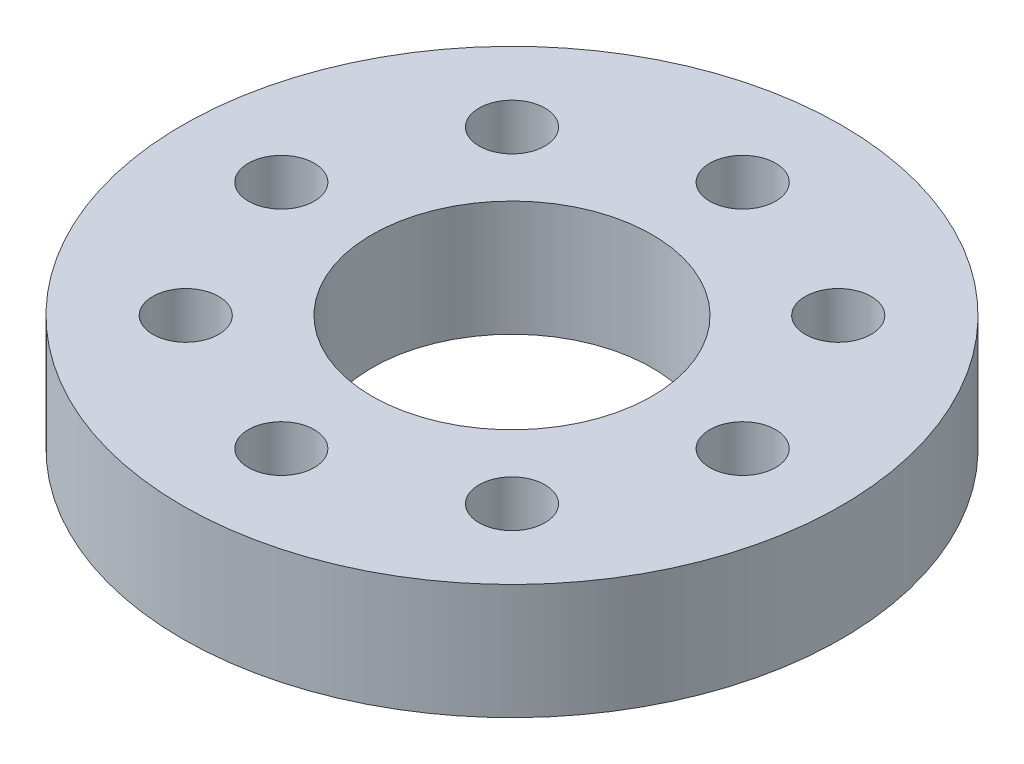
SolidWorks part; units mm, degrees
material "ABS PC"
ref_plane "Front Plane" through (0, 0, 0) normal (0, 0, 1) x (1, 0, 0)
ref_plane "Top Plane" through (0, 0, 0) normal (0, 1, 0) x (1, 0, 0)
ref_plane "Right Plane" through (0, 0, 0) normal (1, 0, 0) x (0, 0, -1)
sketch "Sketch2" plane through (0, 0, 0) normal (0, 1, 0) x (1, 0, 0)
  line L0 (-10.9846, 0) -> (10.9846, 0) construction
  line L1 (0, 5.6811) -> (0, -5.6811) construction
  circle A0 centre (0, 0) radius 10
  circle A1 centre (0, 0) radius 4.25
  circle A2 centre (0, 7) radius 1
  circle A3 centre (4.9497, 4.9497) radius 1
  circle A4 centre (7, 0) radius 1
  circle A5 centre (4.9497, -4.9497) radius 1
  circle A6 centre (0, -7) radius 1
  circle A7 centre (-4.9497, -4.9497) radius 1
  circle A8 centre (-7, 0) radius 1
  circle A9 centre (-4.9497, 4.9497) radius 1
  point P27 (0, 0)
  dimension "D1" = 20
  dimension "D2" = 8.5
  dimension "D4" = 2
  dimension "D3" = 7
  dimension "D5" = 8
extrude "Boss-Extrude1" add sketch "Sketch2" along normal blind 3.5
